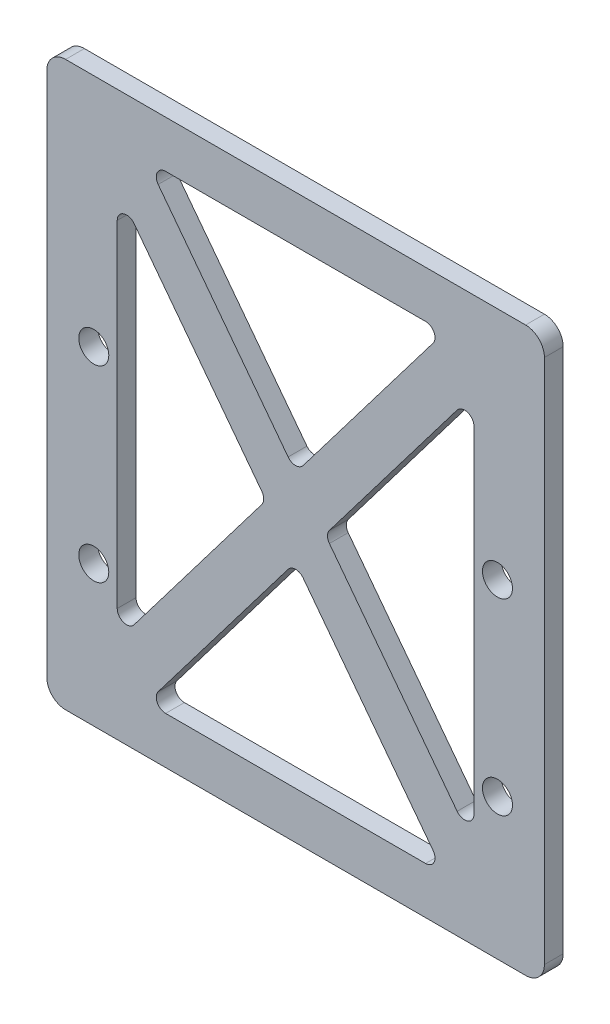
SolidWorks part; units mm, degrees
ref_plane "前视基准面" through (0, 0, 0) normal (0, 0, 1) x (1, 0, 0)
ref_plane "上视基准面" through (0, 0, 0) normal (0, 1, 0) x (1, 0, 0)
ref_plane "右视基准面" through (0, 0, 0) normal (1, 0, 0) x (0, 0, -1)
other "Configuration Table"
sketch "草图1" plane through (0, 0, 0) normal (0, 0, 1) x (1, 0, 0)
  line L1 (-26.5, 30) -> (26.5, 30)
  line L2 (-26.5, 30) -> (-26.5, -30)
  line L3 (-26.5, -30) -> (26.5, -30)
  line L4 (26.5, 30) -> (26.5, -30)
  line L5 (-26.5, 30) -> (26.5, -30) construction
  line L6 (-26.5, -30) -> (26.5, 30) construction
  point P0 (0, 0)
  dimension "D1" = 53
  dimension "D2" = 60
extrude "凸台-拉伸1" add sketch "草图1" along normal blind 2
fillet "圆角1" radius 2 4 edges at (26.5, -30, 1) (-26.5, -30, 1) (-26.5, 30, 1) (26.5, 30, 1)
sketch "草图2" plane through (0, 0, 2) normal (0, 0, 1) x (1, 0, 0)
  circle A0 centre (21.5, 5) radius 1.6
  circle A1 centre (21.5, -15) radius 1.6
  circle A2 centre (-21.5, 5) radius 1.6
  circle A3 centre (-21.5, -15) radius 1.6
extrude "切除-拉伸1" cut sketch "草图2" against normal through all
sketch "草图3" plane through (0, 0, 2) normal (0, 0, 1) x (1, 0, 0)
  line L0 (-26.5, 28) -> (-26.5, -28) construction
  line L1 (-19, 25) -> (19, 25)
  line L2 (-19, 25) -> (-19, -25)
  line L3 (-19, -25) -> (19, -25)
  line L4 (19, 25) -> (19, -25)
  line L5 (26.5, -28) -> (26.5, 28) construction
  line L6 (-24.5, -30) -> (24.5, -30) construction
  line L7 (24.5, 30) -> (-24.5, 30) construction
  line L8 (-19, 25) -> (19, -25) construction
  line L9 (19, 25) -> (-19, -25) construction
  line L10 (17.0096, 26.5127) -> (-20.9904, -23.4873)
  line L11 (-20.9904, 23.4873) -> (17.0096, -26.5127)
  line L12 (20.9904, 23.4873) -> (-17.0096, -26.5127)
  line L13 (-17.0096, 26.5127) -> (20.9904, -23.4873)
  dimension "D1" = 7.5
  dimension "D2" = 7.5
  dimension "D3" = 5
  dimension "D4" = 5
  dimension "D5" = 2.5
  dimension "D6" = 2.5
extrude "切除-拉伸2" cut sketch "草图3" against normal through all contours L11 L2 L10 | L11 L12 L3 | L12 L13 L4 | L1 L13 L10
fillet "圆角2" radius 1 12 edges at (-19, -20.8683, 1) (-19, 20.8683, 1) (-3.1401, 0, 1) (0, 4.1317, 1) (-15.8599, 25, 1) (15.8599, 25, 1) (19, 20.8683, 1) (3.1401, 0, 1) (19, -20.8683, 1) (15.8599, -25, 1) (0, -4.1317, 1) (-15.8599, -25, 1)
